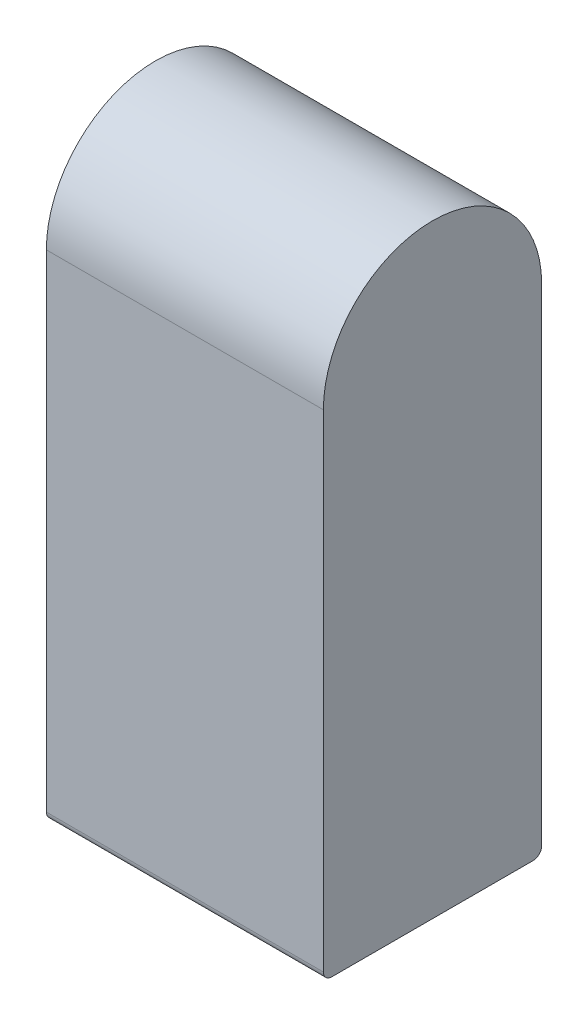
SolidWorks part; units mm, degrees
ref_plane "Alzado" through (0, 0, 0) normal (0, 0, 1) x (1, 0, 0)
ref_plane "Planta" through (0, 0, 0) normal (0, 1, 0) x (1, 0, 0)
ref_plane "Vista lateral" through (0, 0, 0) normal (1, 0, 0) x (0, 0, -1)
sketch "Croquis1" plane through (0, 0, 0) normal (1, 0, 0) x (0, 0, -1)
  line L0 (-12, -30) -> (12, -30)
  line L1 (13, -29) -> (13, 29)
  line L2 (-13, 29) -> (-13, -29)
  arc A0 (13, 29) -> (-13, 29) centre (0, 29) ccw
  arc A1 (12, -30) -> (13, -29) centre (12, -29) ccw
  arc A2 (-12, -30) -> (-13, -29) centre (-12, -29) cw
  point P3 (0, -30)
  point P6 (0, 42)
  point P7 (0, 0)
  point P9 (13, 0)
  point P12 (13, -30)
  point P15 (-13, -30)
  dimension "D3" = 1
  dimension "D1" = 26
  dimension "D2" = 72
extrude "Saliente-Extruir4" add sketch "Croquis1" along normal mid plane 33
